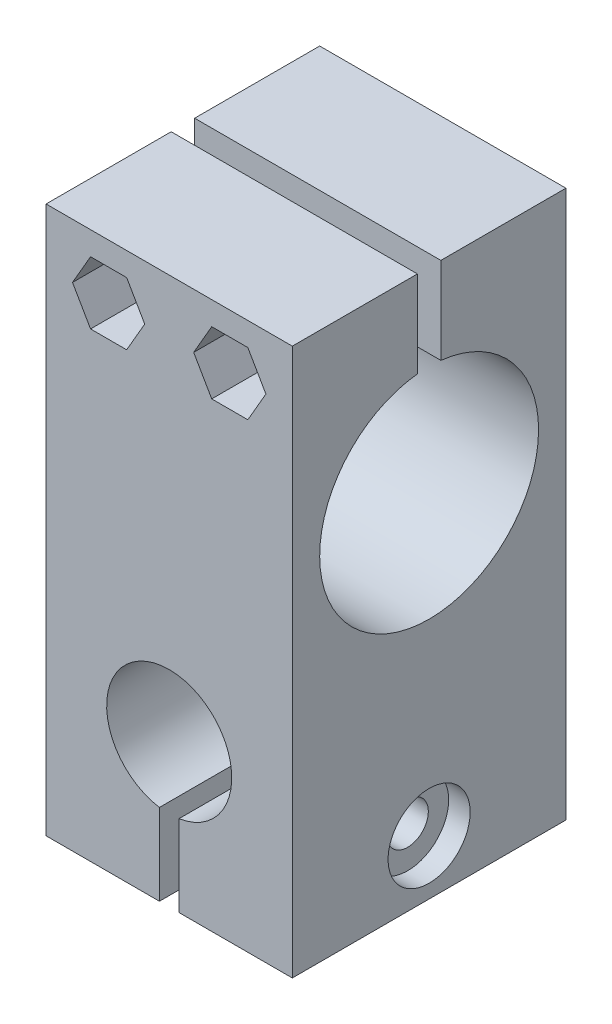
SolidWorks part; units mm, degrees
ref_plane "Plan de face" through (0, 0, 0) normal (0, 0, 1) x (1, 0, 0)
ref_plane "Plan de dessus" through (0, 0, 0) normal (0, 1, 0) x (1, 0, 0)
ref_plane "Plan de droite" through (0, 0, 0) normal (1, 0, 0) x (0, 0, -1)
sketch "Esquisse1" plane through (0, 0, 0) normal (0, 0, 1) x (1, 0, 0)
  line L0 (47.4154, -544.6017) -> (47.4154, -555)
  line L1 (47.4154, -555) -> (61.9154, -555)
  line L2 (61.9154, -555) -> (61.9154, -505)
  line L3 (61.9154, -555) -> (61.9154, -475) construction
  line L4 (61.9154, -505) -> (30.4154, -505)
  line L5 (30.4154, -475) -> (30.4154, -555) construction
  line L6 (30.4154, -505) -> (30.4154, -555)
  line L7 (30.4154, -555) -> (44.9154, -555)
  line L8 (44.9154, -555) -> (44.9154, -544.6017)
  arc A0 (47.4154, -544.6017) -> (44.9154, -544.6017) centre (46.1654, -536.7) ccw
  dimension "D2" = 8
  dimension "D1" = 50
extrude "Boss.-Extru.1" add sketch "Esquisse1" against normal blind 35
sketch "Esquisse4" plane through (61.9154, 0, 0) normal (1, 0, 0) x (0, 0, -1)
  line L0 (35, -505) -> (0, -505) construction
  line L1 (35, -555) -> (0, -555) construction
  line L2 (35, -505) -> (35, -485)
  line L3 (35, -485) -> (19.003, -485)
  line L4 (0, -485) -> (0, -505)
  line L5 (17.5, -476) -> (17.5, -465) construction
  line L6 (16.003, -485) -> (16.003, -496.0803) construction
  line L7 (19.003, -485) -> (19.003, -496.0809) construction
  line L8 (16.003, -485) -> (0, -485)
  line L9 (16.003, -485) -> (19.003, -485)
  line L10 (0, -505) -> (35, -505)
  arc A0 (16.003, -496.0803) -> (19.003, -496.0809) centre (17.5, -510) ccw construction
  circle A1 centre (17.5, -510) radius 14 construction
  point P5 (17.5, -505)
  dimension "D1" = 28
  dimension "D2" = 45
  dimension "D3" = 1.497
  dimension "D4" = 3
  dimension "D5" = 25
extrude "Boss.-Extru.2" add sketch "Esquisse4" against normal up to surface (31.5 mm away) up to face at (30.4154, -530, -17.5)
hole_wizard "Chambrage pour Vis à tête ronde à 6 pans creux M51" positions "Esquisse5" profile "Esquisse6" counterbore size "M5" standard "Ansi Metric"
sketch "Esquisse5" plane through (0, 0, -35) normal (0, 0, -1) x (-1, 0, 0)
  line L0 (-61.9154, -555) -> (-61.9154, -485) construction
  line L1 (-30.4154, -485) -> (-30.4154, -555) construction
  line L2 (-30.4154, -485) -> (-61.9154, -485) construction
  point P0 (-53.9154, -492)
  point P2 (-38.4154, -492)
  dimension "D1" = 8
  dimension "D2" = 8
  dimension "D3" = 7
  dimension "D4" = 7
sketch "Esquisse6" plane through (53.9154, -492, -35) normal (1, 0, 0) x (0, 1, 0)
  line L0 (0, 0) -> (0, 45.5923)
  line L1 (0, 45.5923) -> (2.65, 44)
  line L2 (2.65, 44) -> (2.65, 2.75)
  line L3 (2.65, 2.75) -> (5.25, 2.75)
  line L4 (5.25, 2.75) -> (5.25, 0)
  line L5 (5.25, 0) -> (0, 0)
  line L10 (0, 45.5923) -> (-2.65, 44) construction
  line L11 (0, -6.35) -> (0, 107.95) construction
  dimension "Diamètre du perçage" = 5.3
  dimension "Profondeur du perçage" = 44
  dimension "Diamètre du chambrage" = 10.5
  dimension "Profondeur du chambrage" = 2.75
  dimension "Angle de pointe" = 118
sketch "Esquisse7" plane through (0, 0, 0) normal (0, 0, 1) x (1, 0, 0)
  line L1 (56.2248, -488) -> (51.606, -488)
  line L2 (51.606, -488) -> (49.2966, -492)
  line L3 (49.2966, -492) -> (51.606, -496)
  line L4 (51.606, -496) -> (56.2248, -496)
  line L5 (56.2248, -496) -> (58.5342, -492)
  line L6 (58.5342, -492) -> (56.2248, -488)
  line L7 (40.7248, -488) -> (36.106, -488)
  line L8 (36.106, -488) -> (33.7966, -492)
  line L9 (33.7966, -492) -> (36.106, -496)
  line L10 (36.106, -496) -> (40.7248, -496)
  line L11 (40.7248, -496) -> (43.0342, -492)
  line L12 (43.0342, -492) -> (40.7248, -488)
  circle A0 centre (53.9154, -492) radius 4 construction
  circle A1 centre (38.4154, -492) radius 4 construction
  dimension "D1" = 8
  dimension "D2" = 8
extrude "Enlèv. mat.-Extru.1" cut sketch "Esquisse7" against normal blind 8
sketch "Esquisse8" plane through (61.9154, 0, 0) normal (1, 0, 0) x (0, 0, -1)
  line L0 (16.003, -485) -> (16.003, -496.0803) construction
  line L1 (19.003, -485) -> (19.003, -496.0809) construction
  line L2 (16.003, -485) -> (16.003, -496.0803)
  line L3 (19.003, -485) -> (19.003, -496.0809)
  line L4 (16.003, -485) -> (19.003, -485) construction
  line L5 (16.003, -485) -> (19.003, -485)
  arc A0 (16.003, -496.0803) -> (19.003, -496.0809) centre (17.5, -510) ccw construction
  arc A1 (16.003, -496.0803) -> (19.003, -496.0809) centre (17.5, -510) ccw
extrude "Enlèv. mat.-Extru.2" cut sketch "Esquisse8" against normal blind 45
hole_wizard "Chambrage pour Vis à tête ronde à 6 pans creux M52" positions "Esquisse9" profile "Esquisse10" counterbore size "M5" standard "Ansi Metric"
sketch "Esquisse9" plane through (61.9154, 0, 0) normal (1, 0, 0) x (0, 0, -1)
  line L0 (35, -555) -> (0, -555) construction
  point P0 (17.5, -548)
  point P6 (17.5, -555)
  dimension "D1" = 7
sketch "Esquisse10" plane through (61.9154, -548, -17.5) normal (0, 1, 0) x (0, 0, -1)
  line L0 (0, 0) -> (0, 45.5923)
  line L1 (0, 45.5923) -> (2.65, 44)
  line L2 (2.65, 44) -> (2.65, 2.75)
  line L3 (2.65, 2.75) -> (5.25, 2.75)
  line L4 (5.25, 2.75) -> (5.25, 0)
  line L5 (5.25, 0) -> (0, 0)
  line L10 (0, 45.5923) -> (-2.65, 44) construction
  line L11 (0, -6.35) -> (0, 107.95) construction
  dimension "Diamètre du perçage" = 5.3
  dimension "Profondeur du perçage" = 44
  dimension "Diamètre du chambrage" = 10.5
  dimension "Profondeur du chambrage" = 2.75
  dimension "Angle de pointe" = 118
sketch "Esquisse11" plane through (30.4154, 0, 0) normal (-1, 0, 0) x (0, 0, 1)
  line L1 (-15.1906, -544) -> (-19.8094, -544)
  line L2 (-19.8094, -544) -> (-22.1188, -548)
  line L3 (-22.1188, -548) -> (-19.8094, -552)
  line L4 (-19.8094, -552) -> (-15.1906, -552)
  line L5 (-15.1906, -552) -> (-12.8812, -548)
  line L6 (-12.8812, -548) -> (-15.1906, -544)
  circle A0 centre (-17.5, -548) radius 4 construction
  dimension "D1" = 8
extrude "Enlèv. mat.-Extru.3" cut sketch "Esquisse11" against normal blind 6
sketch "Esquisse12" plane through (0, -555, 0) normal (0, -1, 0) x (1, 0, 0)
  line L0 (61.9154, -35) -> (61.9154, 0) construction
  line L1 (47.4154, -35) -> (61.9154, -35) construction
  circle A0 centre (56.9154, -31) radius 1.4
  dimension "D1" = 2.8
  dimension "D2" = 5
  dimension "D3" = 4
extrude "Enlèv. mat.-Extru.4" cut sketch "Esquisse12" against normal blind 5
